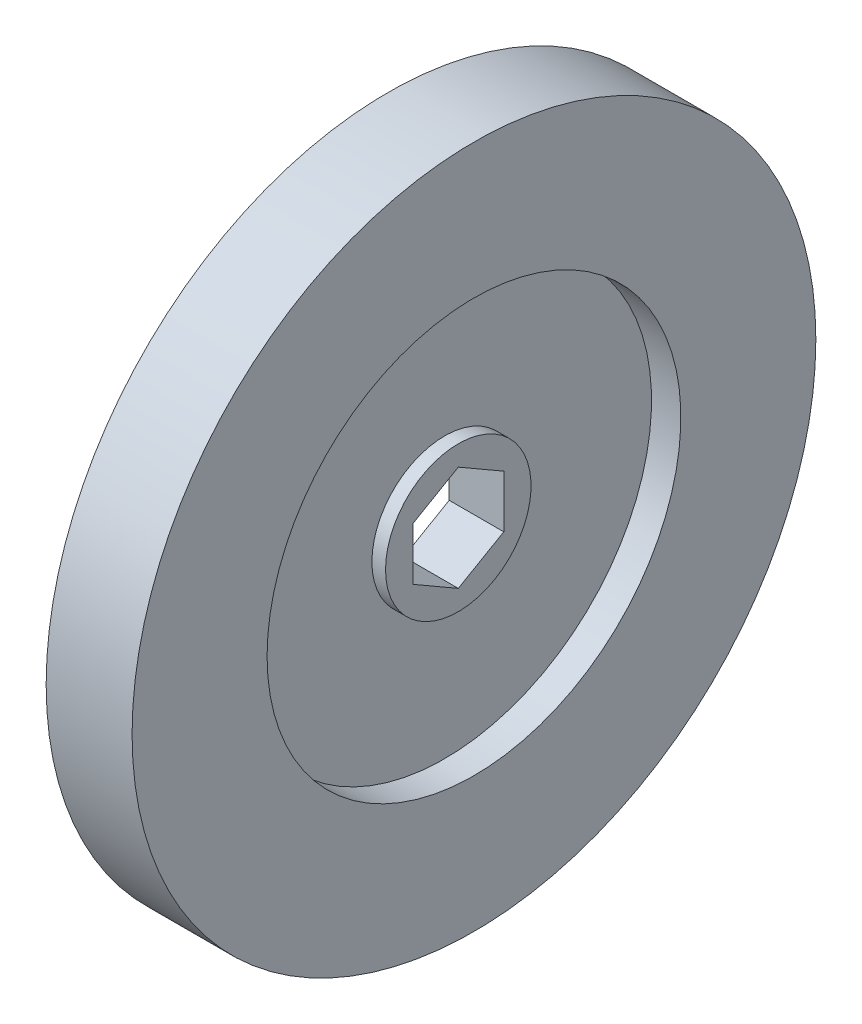
SolidWorks part; units mm, degrees
ref_plane "Plan de face" through (0, 0, 0) normal (0, 0, 1) x (1, 0, 0)
ref_plane "Plan de dessus" through (0, 0, 0) normal (0, 1, 0) x (1, 0, 0)
ref_plane "Plan de droite" through (0, 0, 0) normal (1, 0, 0) x (0, 0, -1)
sketch "Esquisse1" plane through (0, 0, 0) normal (0, 0, 1) x (1, 0, 0)
  line L0 (-12.566, 0) -> (17.5241, 0) construction
  line L1 (-6, 47.7465) -> (6, 47.7465)
  line L2 (6, 47.7465) -> (6, 28.8925)
  line L3 (6, 28.8925) -> (1.905, 28.8925)
  line L4 (1.905, 28.8925) -> (1.905, 10.16)
  line L5 (1.905, 10.16) -> (3.81, 10.16)
  line L6 (3.81, 10.16) -> (3.81, 0)
  line L7 (3.81, 0) -> (-3.81, 0)
  line L8 (0, 0) -> (0, 49.4244) construction
  line L9 (-3.81, 10.16) -> (-3.81, 0)
  line L10 (-1.905, 10.16) -> (-3.81, 10.16)
  line L11 (-1.905, 28.8925) -> (-1.905, 10.16)
  line L12 (-6, 28.8925) -> (-1.905, 28.8925)
  line L13 (-6, 47.7465) -> (-6, 28.8925)
  point P18 (0, 47.7465)
  dimension "D1" = 12
  dimension "D2" = 7.62
  dimension "D3" = 3.81
  dimension "D4" = 95.493
  dimension "D5" = 20.32
  dimension "D6" = 57.785
revolve "Révolution1" add sketch "Esquisse1" angle 360 about L0
sketch "Esquisse2" plane through (3.81, 0, 0) normal (1, 0, 0) x (0, 0, -1)
  line L1 (0, 7.3323) -> (-6.35, 3.6662)
  line L2 (-6.35, 3.6662) -> (-6.35, -3.6662)
  line L3 (-6.35, -3.6662) -> (0, -7.3323)
  line L4 (0, -7.3323) -> (6.35, -3.6662)
  line L5 (6.35, -3.6662) -> (6.35, 3.6662)
  line L6 (6.35, 3.6662) -> (0, 7.3323)
  circle A0 centre (0, 0) radius 6.35 construction
  dimension "D1" = 12.7
extrude "Enlèv. mat.-Extru.1" cut sketch "Esquisse2" against normal through all
